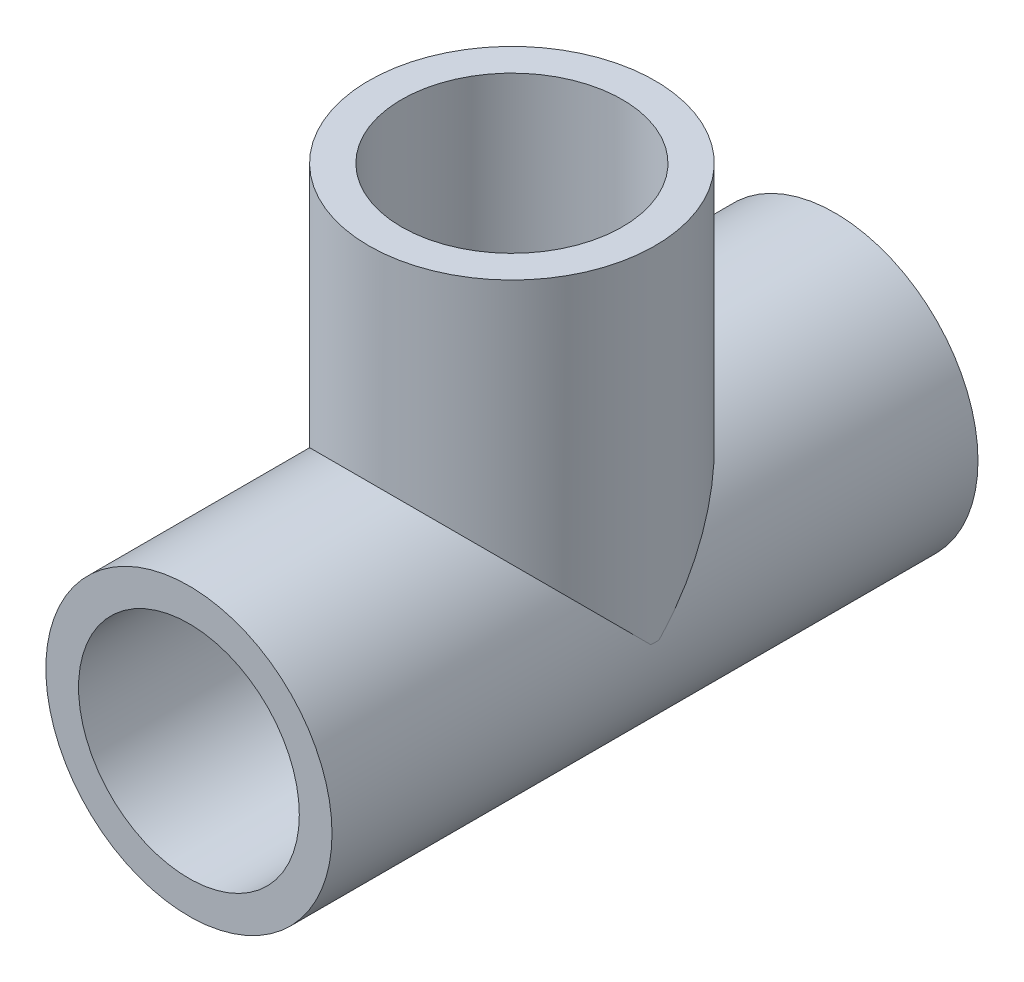
SolidWorks part; units mm, degrees
material "PVC Rigid"
ref_plane "Front Plane" through (0, 0, 0) normal (0, 0, 1) x (1, 0, 0)
ref_plane "Top Plane" through (0, 0, 0) normal (0, 1, 0) x (1, 0, 0)
ref_plane "Right Plane" through (0, 0, 0) normal (1, 0, 0) x (0, 0, -1)
sketch "Sketch1" plane through (0, 0, 0) normal (0, 0, 1) x (1, 0, 0)
  circle A0 centre (0, 0) radius 13.5
  circle A1 centre (0, 0) radius 17.5
  dimension "D1" = 27
  dimension "D2" = 35
sketch3d "3DSketch3"
  line L0 (0, 0, 0) -> (0, 0, -79)
  dimension "D1" = 79
sweep "Sweep1" add profiles "Sketch1" path "3DSketch3"
ref_plane "Plane1" through (0, 17.5, 0) normal (0, 1, 0) x (1, 0, 0)
sketch "Sketch2" plane through (0, 17.5, 0) normal (0, 1, 0) x (1, 0, 0)
  line L0 (0, 0) -> (0, 79) construction
  circle A0 centre (0, 39.5) radius 17.5
  dimension "D1" = 35
extrude "Boss-Extrude2" add sketch "Sketch2" along normal blind 25 and the other way blind 17
sketch "Sketch3" plane through (0, 0, 0) normal (0, 0, 1) x (1, 0, 0)
  circle A2 centre (0, 0) radius 13.5 construction
  circle A3 centre (0, 0) radius 13.5
extrude "Cut-Extrude1" cut sketch "Sketch3" against normal through all
sketch "Sketch4" plane through (0, 42.5, 0) normal (0, 1, 0) x (1, 0, 0)
  circle A0 centre (0, 39.5) radius 13.5
  dimension "D1" = 27
extrude "Cut-Extrude2" cut sketch "Sketch4" against normal up to next
